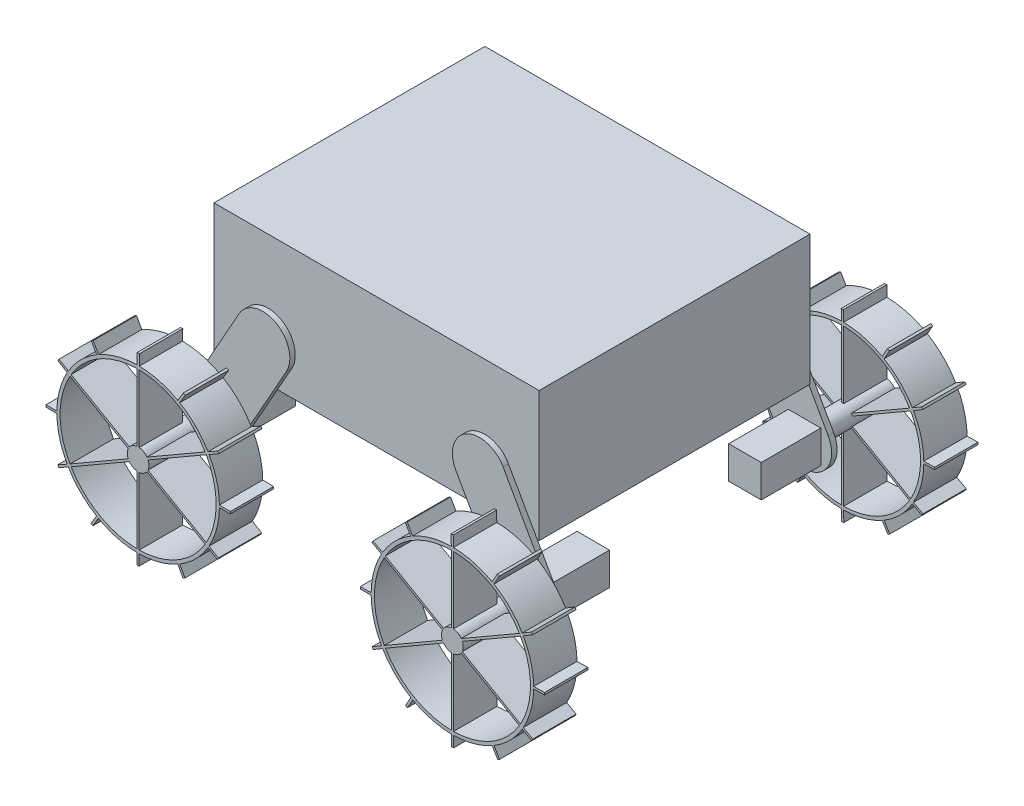
SolidWorks part; units mm, degrees
material "7075-T6 (SN)"
ref_plane "Front Plane" through (0, 0, 0) normal (0, 0, 1) x (1, 0, 0)
ref_plane "Top Plane" through (0, 0, 0) normal (0, 1, 0) x (1, 0, 0)
ref_plane "Right Plane" through (0, 0, 0) normal (1, 0, 0) x (0, 0, -1)
sketch "Sketch1" plane through (0, 0, 0) normal (0, 1, 0) x (1, 0, 0)
  line L0 (-149, -124) -> (149, -124)
  line L1 (-150, -125) -> (150, -125)
  line L2 (-150, -125) -> (-150, 125)
  line L3 (-150, 125) -> (150, 125)
  line L4 (150, -125) -> (150, 125)
  line L5 (-150, -125) -> (150, 125) construction
  line L6 (-150, 125) -> (150, -125) construction
  line L7 (149, -124) -> (149, 124)
  line L8 (-149, 124) -> (149, 124)
  line L9 (-149, -124) -> (-149, 124)
  point P0 (0, 0)
  dimension "D1" = 1
extrude "Boss-Extrude1" add sketch "Sketch1" along normal blind 120
sketch "Sketch2" plane through (0, 0, 0) normal (0, 1, 0) x (1, 0, 0)
  line L1 (-149, -124) -> (149, -124)
  line L2 (-149, -124) -> (-149, 124)
  line L3 (-149, 124) -> (149, 124)
  line L4 (149, -124) -> (149, 124)
  line L5 (-149, -124) -> (149, 124) construction
  line L6 (-149, 124) -> (149, -124) construction
  point P0 (0, 0)
extrude "Boss-Extrude2" add sketch "Sketch2" along normal blind 1
sketch "Sketch3" plane through (0, 120, 0) normal (0, 1, 0) x (1, 0, 0)
  line L1 (-149, -124) -> (149, -124)
  line L2 (-149, -124) -> (-149, 124)
  line L3 (-149, 124) -> (149, 124)
  line L4 (149, -124) -> (149, 124)
  line L5 (-149, -124) -> (149, 124) construction
  line L6 (-149, 124) -> (149, -124) construction
  point P0 (0, 0)
extrude "Boss-Extrude3" add sketch "Sketch3" against normal blind 1
sketch "Sketch4" plane through (0, 0, 125) normal (0, 0, 1) x (1, 0, 0)
  line L0 (-166.7894, -31.9645) -> (-121.7894, 48.0355)
  line L1 (-150, 0) -> (-125, 0) construction
  line L2 (-150, 0) -> (-150, 35.7789) construction
  line L3 (-150, 35.7789) -> (-100, 35.7789) construction
  line L4 (-100, 0) -> (-100, 35.7789) construction
  line L5 (150, 0) -> (145, 0) construction
  line L6 (150, 0) -> (150, 35) construction
  line L7 (150, 35) -> (125, 35) construction
  line L8 (100, 0) -> (100, 35) construction
  line L13 (166.7894, -32.7435) -> (121.7894, 47.2565)
  line L14 (-100, 35.7789) -> (-125, 35.7789) construction
  line L18 (100, 35) -> (145, 35) construction
  line L19 (100, 35) -> (100, -45) construction
  line L20 (100, -45) -> (145, -45) construction
  line L21 (145, 35) -> (145, -45) construction
  line L22 (123.2106, -57.2565) -> (78.2106, 22.7435)
  line L23 (-100, 35.7789) -> (-150, 35.7789) construction
  line L24 (-100, 35.7789) -> (-145, 35.7789) construction
  line L25 (-100, 35.7789) -> (-100, -44.2211) construction
  line L26 (-100, -44.2211) -> (-145, -44.2211) construction
  line L27 (-145, 35.7789) -> (-145, -44.2211) construction
  line L28 (-100, 35.7789) -> (-100, 0) construction
  line L29 (-100, 0) -> (-150, 0) construction
  line L30 (-150, 35.7789) -> (-150, 0) construction
  line L31 (-123.2106, -56.4776) -> (-78.2106, 23.5224)
  arc A0 (-75, 35.7789) -> (-121.7894, 48.0355) centre (-100, 35.7789) ccw
  arc A1 (121.7894, 47.2565) -> (75, 35) centre (100, 35) ccw
  arc A2 (123.2106, -57.2565) -> (166.7894, -32.7435) centre (145, -45) ccw
  arc A3 (-78.2106, 23.5224) -> (-121.7894, 48.0355) centre (-100, 35.7789) ccw
  arc A4 (121.7894, 47.2565) -> (78.2106, 22.7435) centre (100, 35) ccw
  arc A5 (-166.7894, -31.9645) -> (-123.2106, -56.4776) centre (-145, -44.2211) ccw
  line M27 (-150, 0) -> (150, 0)
extrude "Boss-Extrude4" add sketch "Sketch4" along normal blind 5 contours L0 A5 L31 M27 | L31 A3 A0 L0 M27 | A1 A4 L22 L13 M27 | L22 A2 L13 M27
sketch "Sketch6" plane through (0, 0, 130) normal (0, 0, 1) x (1, 0, 0)
  circle A0 centre (145, -45) radius 10
extrude "Boss-Extrude6" add sketch "Sketch6" along normal blind 30
sketch "Sketch5" plane through (0, 0, 160) normal (0, 0, 1) x (1, 0, 0)
  line L0 (218.0148, -1.4818) -> (219.0388, -3.1998)
  line L1 (209.4249, -6.6016) -> (218.0148, -1.4818)
  line L2 (219.0388, -3.1998) -> (210.4259, -8.3332)
  line L3 (229.9918, -43.8196) -> (230.0196, -45.8194)
  line L4 (230.0196, -45.8194) -> (219.9939, -45.9586)
  line L5 (219.9928, -43.9584) -> (229.9918, -43.8196)
  line L6 (219.1953, -86.4736) -> (218.2194, -88.2194)
  line L7 (218.2194, -88.2194) -> (209.4673, -83.3271)
  line L8 (210.4664, -81.5944) -> (219.1953, -86.4736)
  line L9 (188.5182, -118.0148) -> (186.8002, -119.0388)
  line L10 (186.8002, -119.0388) -> (181.6668, -110.4259)
  line L11 (183.3984, -109.4249) -> (188.5182, -118.0148)
  line L12 (146.1804, -129.9918) -> (144.1806, -130.0196)
  line L13 (144, -43.2679) -> (144, 27)
  line L14 (144.1806, -130.0196) -> (144.0414, -119.9939)
  line L15 (144, -43.2679) -> (83.1462, -8.134)
  line L16 (146.0416, -119.9928) -> (146.1804, -129.9918)
  line L17 (146, -43.2679) -> (206.8538, -8.134)
  line L18 (146, -43.2679) -> (146, 27)
  line L19 (103.5264, -119.1953) -> (101.7806, -118.2194)
  line L20 (147, -45) -> (207.8538, -80.134)
  line L21 (147, -45) -> (207.8538, -9.866)
  line L22 (146, -46.7321) -> (146, -117)
  line L23 (146, -46.7321) -> (206.8538, -81.866)
  line L24 (144, -46.7321) -> (83.1462, -81.866)
  line L25 (144, -46.7321) -> (144, -117)
  line L26 (143, -45) -> (82.1462, -9.866)
  line L27 (143, -45) -> (82.1462, -80.134)
  line L28 (101.7806, -118.2194) -> (106.6729, -109.4673)
  line L29 (108.4056, -110.4664) -> (103.5264, -119.1953)
  line L30 (71.9852, -88.5182) -> (70.9612, -86.8002)
  line L31 (70.9612, -86.8002) -> (79.5741, -81.6668)
  line L32 (80.5751, -83.3984) -> (71.9852, -88.5182)
  line L33 (60.0082, -46.1804) -> (59.9804, -44.1806)
  line L34 (59.9804, -44.1806) -> (70.0061, -44.0414)
  line L35 (70.0072, -46.0416) -> (60.0082, -46.1804)
  line L36 (70.8047, -3.5264) -> (71.7806, -1.7806)
  line L37 (71.7806, -1.7806) -> (80.5327, -6.6729)
  line L38 (79.5336, -8.4056) -> (70.8047, -3.5264)
  line L39 (101.4818, 28.0148) -> (103.1998, 29.0388)
  line L40 (103.1998, 29.0388) -> (108.3332, 20.4259)
  line L41 (106.6016, 19.4249) -> (101.4818, 28.0148)
  line L42 (143.8196, 39.9918) -> (145.8194, 40.0196)
  line L43 (145.8194, 40.0196) -> (145.9586, 29.9939)
  line L44 (143.9584, 29.9928) -> (143.8196, 39.9918)
  line L45 (186.4736, 29.1953) -> (188.2194, 28.2194)
  line L46 (188.2194, 28.2194) -> (183.3271, 19.4673)
  line L47 (181.5944, 20.4664) -> (186.4736, 29.1953)
  arc A1 (144, 26.9931) -> (83.1522, -8.1374) centre (145, -45) ccw
  arc A3 (106.6016, 19.4249) -> (80.5327, -6.6729) centre (145, -45) ccw
  arc A4 (82.1522, -9.8695) -> (82.1522, -80.1305) centre (145, -45) ccw
  arc A5 (83.1522, -81.8626) -> (144, -116.9931) centre (145, -45) ccw
  arc A6 (146, -116.9931) -> (206.8478, -81.8626) centre (145, -45) ccw
  arc A7 (207.8478, -80.1305) -> (207.8478, -9.8695) centre (145, -45) ccw
  arc A8 (206.8478, -8.1374) -> (146, 26.9931) centre (145, -45) ccw
  arc A9 (143.9584, 29.9928) -> (108.3332, 20.4259) centre (145, -45) ccw
  arc A10 (181.5944, 20.4664) -> (145.9586, 29.9939) centre (145, -45) ccw
  arc A11 (209.4249, -6.6016) -> (183.3271, 19.4673) centre (145, -45) ccw
  arc A12 (219.9928, -43.9584) -> (210.4259, -8.3332) centre (145, -45) ccw
  arc A13 (210.4664, -81.5944) -> (219.9939, -45.9586) centre (145, -45) ccw
  arc A14 (183.3984, -109.4249) -> (209.4673, -83.3271) centre (145, -45) ccw
  arc A15 (146.0416, -119.9928) -> (181.6668, -110.4259) centre (145, -45) ccw
  arc A16 (108.4056, -110.4664) -> (144.0414, -119.9939) centre (145, -45) ccw
  arc A17 (80.5751, -83.3984) -> (106.6729, -109.4673) centre (145, -45) ccw
  arc A18 (70.0072, -46.0416) -> (79.5741, -81.6668) centre (145, -45) ccw
  arc A19 (79.5336, -8.4056) -> (70.0061, -44.0414) centre (145, -45) ccw
  dimension "D1" = 12
extrude "Boss-Extrude5" add sketch "Sketch5" along normal blind 40
sketch "Sketch7" plane through (0, 0, 160) normal (0, 0, 1) x (1, 0, 0)
  circle A0 centre (145, -45) radius 10 construction
  circle A4 centre (145, -45) radius 10
extrude "Boss-Extrude7" add sketch "Sketch7" along normal blind 40
sketch "Sketch11" plane through (0, 0, 125) normal (0, 0, 1) x (1, 0, 0)
  line L1 (0, 120) -> (150, 120) construction
  line L2 (-150, 120) -> (150, 120) construction
  line L3 (150, 120) -> (0, 120) construction
  line L4 (-150, 120) -> (0, 120) construction
  line L5 (100, 35) -> (-100, 35.7789) construction
  line L6 (0, 120) -> (0, 0) construction
  line L7 (-145, -44.2211) -> (-100, -44.2211) construction
  line L8 (-145, -44.2211) -> (-145, 35.7789) construction
  line L9 (-145, 35.7789) -> (-100, 35.7789) construction
  line L10 (-100, -44.2211) -> (-100, 35.7789) construction
  line L11 (145, -45) -> (100, -45) construction
  line L12 (145, -45) -> (145, 35) construction
  line L13 (145, 35) -> (100, 35) construction
  line L14 (100, -45) -> (100, 35) construction
  arc A0 (-166.7894, -31.9645) -> (-123.2106, -56.4776) centre (-145, -44.2211) ccw construction
  arc A1 (-166.7894, -31.9645) -> (-123.2106, -56.4776) centre (-145, -44.2211) ccw construction
mirror "Mirror8" about plane through (0, 0, 0) normal (1, 0, 0) of "Boss-Extrude7", "Boss-Extrude5", "Boss-Extrude6"
mirror "Mirror9" about plane through (0, 0, 0) normal (0, 0, 1) of "Boss-Extrude4", "Boss-Extrude7", "Boss-Extrude6", "Mirror8", "Boss-Extrude5"
sketch "Sketch13" plane through (0, 0, -125) normal (0, 0, 1) x (1, 0, 0)
  line L6 (130, -60) -> (160, -60)
  line L7 (130, -60) -> (130, -30)
  line L8 (130, -30) -> (160, -30)
  line L9 (160, -60) -> (160, -30)
  line L10 (130, -60) -> (160, -30) construction
  line L11 (130, -30) -> (160, -60) construction
  point P0 (145, -45)
extrude "Boss-Extrude9" add sketch "Sketch13" along normal blind 55
mirror "Mirror10" about plane through (0, 0, 0) normal (1, 0, 0) of "Boss-Extrude9"
mirror "Mirror11" about plane through (0, 0, 0) normal (0, 0, 1) of "Mirror10", "Boss-Extrude9"
